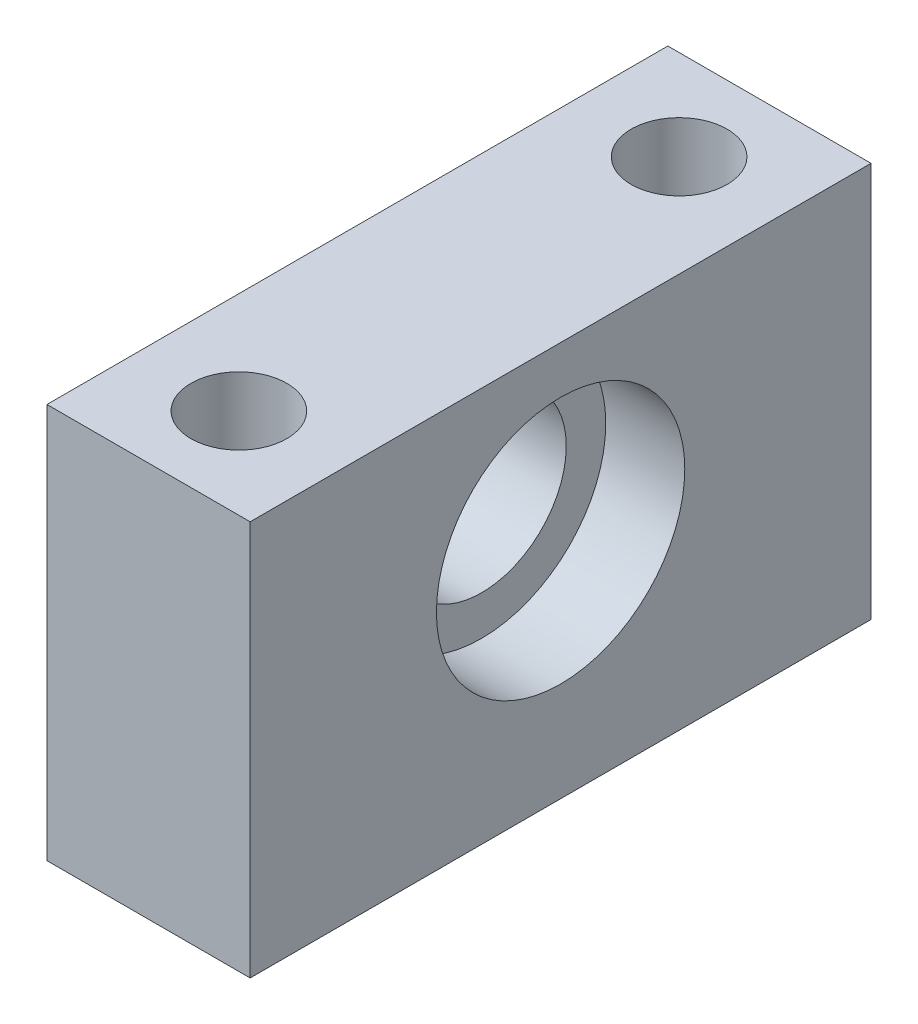
SolidWorks part; units mm, degrees
ref_plane "Plan de face" through (0, 0, 0) normal (0, 0, 1) x (1, 0, 0)
ref_plane "Plan de dessus" through (0, 0, 0) normal (0, 1, 0) x (1, 0, 0)
ref_plane "Plan de droite" through (0, 0, 0) normal (1, 0, 0) x (0, 0, -1)
sketch "Esquisse1" plane through (0, 0, 0) normal (1, 0, 0) x (0, 0, -1)
  line L1 (-295.6715, -19.286) -> (-240.6715, -19.286)
  line L2 (-295.6715, -19.286) -> (-295.6715, -54.286)
  line L3 (-295.6715, -54.286) -> (-240.6715, -54.286)
  line L4 (-240.6715, -19.286) -> (-240.6715, -54.286)
  dimension "D1" = 55
  dimension "D2" = 35
extrude "Boss.-Extru.1" add sketch "Esquisse1" along normal blind 18
sketch "Esquisse2" plane through (18, 0, 0) normal (1, 0, 0) x (0, 0, -1)
  line L0 (-240.6715, -54.286) -> (-240.6715, -19.286) construction
  line L1 (-240.6715, -19.286) -> (-295.6715, -19.286) construction
  circle A0 centre (-268.1715, -34.4858) radius 11
  dimension "D3" = 22
  dimension "D1" = 27.5
  dimension "D2" = 15.1998
extrude "Enlèv. mat.-Extru.1" cut sketch "Esquisse2" against normal blind 7
sketch "Esquisse3" plane through (0, 0, 0) normal (-1, 0, 0) x (0, 0, 1)
  line L0 (240.6715, -54.286) -> (240.6715, -19.286) construction
  line L1 (240.6715, -19.286) -> (295.6715, -19.286) construction
  circle A0 centre (268.1715, -34.4858) radius 7.5
  dimension "D1" = 15
  dimension "D2" = 27.5
  dimension "D3" = 15.1998
extrude "Enlèv. mat.-Extru.2" cut sketch "Esquisse3" against normal through all
sketch "Esquisse4" plane through (0, -19.286, 0) normal (0, 1, 0) x (1, 0, 0)
  circle A0 centre (9, -287.6715) radius 2
  circle A1 centre (9, -248.6715) radius 2
extrude "Enlèv. mat.-Extru.3" cut sketch "Esquisse4" against normal through all
sketch "Esquisse5" plane through (0, -19.286, 0) normal (0, 1, 0) x (1, 0, 0)
  circle A0 centre (9, -287.6715) radius 4.25
  circle A1 centre (9, -248.6715) radius 4.25
  dimension "D1" = 8.5
extrude "Enlèv. mat.-Extru.4" cut sketch "Esquisse5" against normal blind 12
